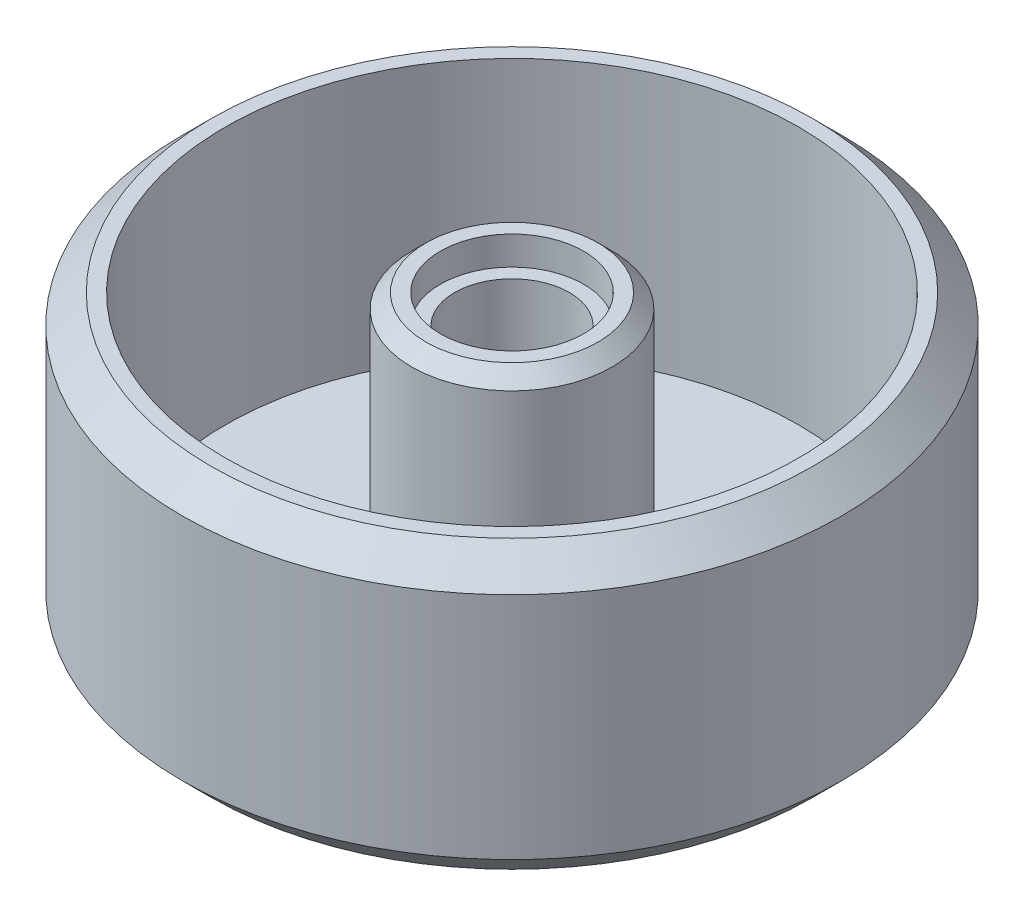
SolidWorks part; units mm, degrees
ref_plane "前视基准面" through (0, 0, 0) normal (0, 0, 1) x (1, 0, 0)
ref_plane "上视基准面" through (0, 0, 0) normal (0, 1, 0) x (1, 0, 0)
ref_plane "右视基准面" through (0, 0, 0) normal (1, 0, 0) x (0, 0, -1)
sketch "草图1" plane through (0, 0, 0) normal (0, 1, 0) x (1, 0, 0)
  circle A0 centre (0, 0) radius 11.5
  dimension "D1" = 23
extrude "凸台-拉伸1" add sketch "草图1" along normal blind 10
sketch "草图2" plane through (0, 10, 0) normal (0, 1, 0) x (1, 0, 0)
  circle A0 centre (0, 0) radius 10
  circle A1 centre (0, 0) radius 3.5
  dimension "D1" = 20
  dimension "D2" = 7
extrude "切除-拉伸1" cut sketch "草图2" against normal blind 9
sketch "草图3" plane through (0, 10, 0) normal (0, 1, 0) x (1, 0, 0)
  circle A0 centre (0, 0) radius 2.5
  dimension "D1" = 5
extrude "切除-拉伸2" cut sketch "草图3" against normal blind 1
sketch "草图4" plane through (0, 0, 0) normal (0, -1, 0) x (1, 0, 0)
  circle A0 centre (0, 0) radius 2.5
  dimension "D1" = 5
extrude "切除-拉伸3" cut sketch "草图4" against normal blind 1
sketch "草图5" plane through (0, 1, 0) normal (0, -1, 0) x (1, 0, 0)
  circle A0 centre (0, 0) radius 2
  dimension "D1" = 4
extrude "切除-拉伸4" cut sketch "草图5" against normal through all
chamfer "倒角1" distance 1 angle 45 2 edges at (0, 0, 11.5) (0, 10, 11.5)
chamfer "倒角2" distance 0.5 angle 45 1 edges at (0, 10, 3.5)
